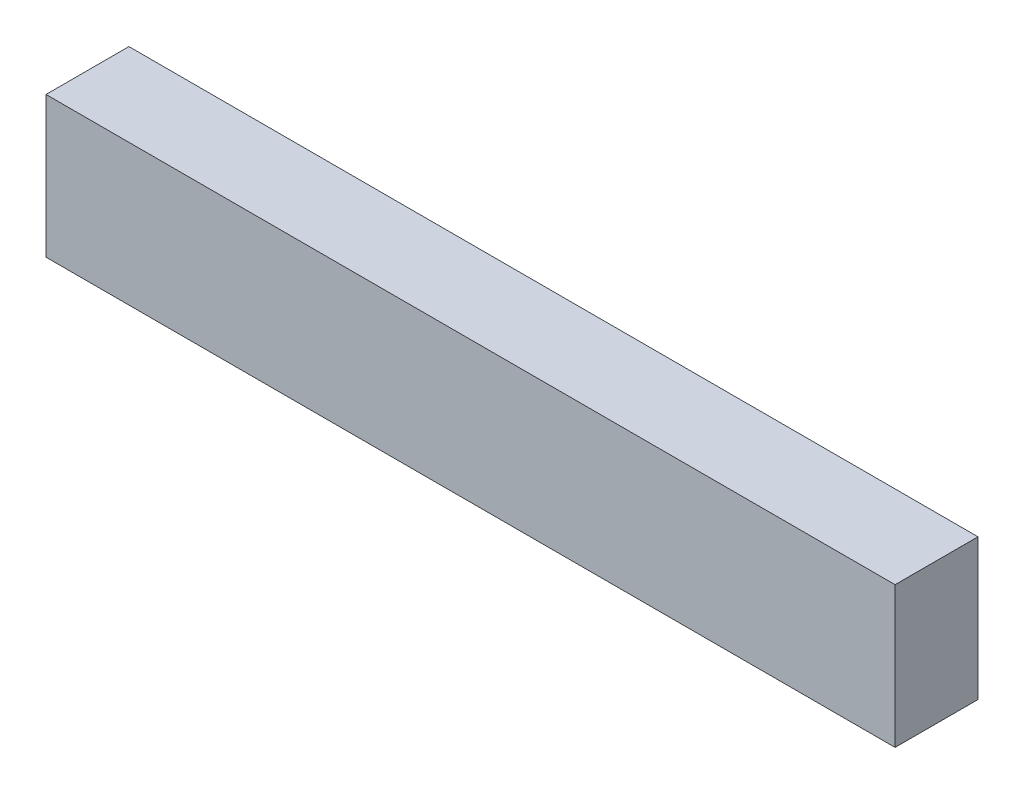
SolidWorks part; units mm, degrees
ref_plane "Front Plane" through (0, 0, 0) normal (0, 0, 1) x (1, 0, 0)
ref_plane "Top Plane" through (0, 0, 0) normal (0, 1, 0) x (1, 0, 0)
ref_plane "Right Plane" through (0, 0, 0) normal (1, 0, 0) x (0, 0, -1)
sketch "Sketch1" plane through (0, 0, 0) normal (0, 1, 0) x (1, 0, 0)
  line L1 (-25.6, 2.5) -> (25.6, 2.5)
  line L2 (-25.6, 2.5) -> (-25.6, -2.5)
  line L3 (-25.6, -2.5) -> (25.6, -2.5)
  line L4 (25.6, 2.5) -> (25.6, -2.5)
  line L5 (-25.6, 2.5) -> (25.6, -2.5) construction
  line L6 (-25.6, -2.5) -> (25.6, 2.5) construction
  point P0 (0, 0)
  dimension "D1" = 5
  dimension "D2" = 51.2
extrude "Boss-Extrude1" add sketch "Sketch1" along normal blind 8.5
